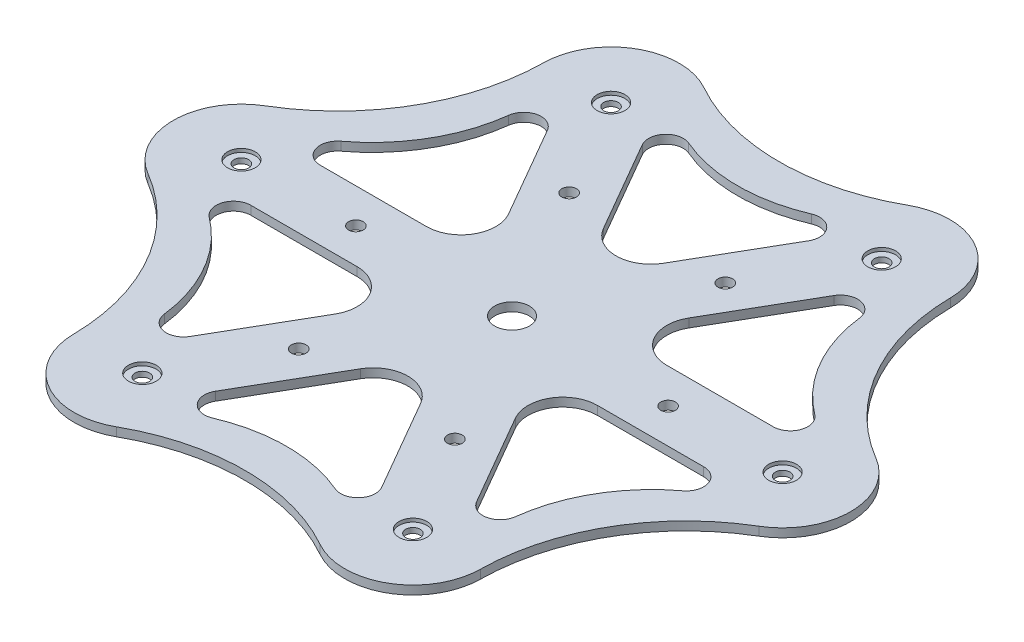
SolidWorks part; units mm, degrees
ref_plane "前视基准面" through (0, 0, 0) normal (0, 0, 1) x (1, 0, 0)
ref_plane "上视基准面" through (0, 0, 0) normal (0, 1, 0) x (1, 0, 0)
ref_plane "右视基准面" through (0, 0, 0) normal (1, 0, 0) x (0, 0, -1)
other "Configuration Table"
sketch "草图2" plane through (0, 0, 0) normal (0, 1, 0) x (1, 0, 0)
  line L1 (45, 0) -> (22.5, 38.9711)
  line L2 (22.5, 38.9711) -> (-22.5, 38.9711)
  line L3 (-22.5, 38.9711) -> (-45, 0)
  line L4 (-45, 0) -> (-22.5, -38.9711)
  line L5 (-22.5, -38.9711) -> (22.5, -38.9711)
  line L6 (22.5, -38.9711) -> (45, 0)
  line L7 (-54.5, 0) -> (-27.25, -47.1984)
  line L8 (-27.25, -47.1984) -> (27.25, -47.1984)
  line L9 (27.25, -47.1984) -> (54.5, 0)
  line L10 (54.5, 0) -> (27.25, 47.1984)
  line L11 (27.25, 47.1984) -> (-27.25, 47.1984)
  line L12 (-27.25, 47.1984) -> (-54.5, 0)
  circle A0 centre (0, 0) radius 38.9711 construction
  circle A1 centre (0, 0) radius 47.1984 construction
  circle A2 centre (0, 0) radius 5
  dimension "D3" = 10
  dimension "D1" = 45
  dimension "D2" = 9.5
extrude "凸台-拉伸1" add sketch "草图2" along normal blind 2.5 contours L5 L6 L1 L2 L3 L4 | L11 L12 L7 L8 L9 L10 L6 L5 L4 L3 L2 L1
sketch "草图3" plane through (0, 2.5, 0) normal (0, 1, 0) x (1, 0, 0)
  line L7 (-45, 0) -> (-22.5, -38.9711) construction
  line L8 (-22.5, -38.9711) -> (22.5, -38.9711) construction
  line L9 (22.5, -38.9711) -> (45, 0) construction
  line L10 (45, 0) -> (22.5, 38.9711) construction
  line L11 (22.5, 38.9711) -> (-22.5, 38.9711) construction
  line L12 (-22.5, 38.9711) -> (-45, 0) construction
  circle A0 centre (0, 0) radius 38.9711 construction
  circle A7 centre (-22.5, 38.9711) radius 2.1
  circle A8 centre (22.5, 38.9711) radius 2.1
  circle A9 centre (45, 0) radius 2.1
  circle A10 centre (22.5, -38.9711) radius 2.1
  circle A11 centre (-22.5, -38.9711) radius 2.1
  circle A12 centre (-45, 0) radius 2.1
  point P23 (0, 0)
  point P24 (0, 0)
  dimension "D2" = 4.2
  dimension "D1" = 45
  dimension "D3" = 6
extrude "切除-拉伸1" cut sketch "草图3" against normal blind 2.5
sketch "草图4" plane through (0, 2.5, 0) normal (0, 1, 0) x (1, 0, 0)
  line L0 (-27.25, 47.1984) -> (-54.5, 0) construction
  line L1 (-54.5, 0) -> (-27.25, -47.1984)
  line L2 (-27.25, -47.1984) -> (27.25, -47.1984)
  line L3 (27.25, -47.1984) -> (54.5, 0)
  line L4 (54.5, 0) -> (27.25, 47.1984)
  line L5 (27.25, 47.1984) -> (-27.25, 47.1984)
  line L6 (-27.25, 47.1984) -> (-54.5, 0)
  line L7 (-100.688, 0) -> (-50.344, -87.1984)
  line L8 (-50.344, -87.1984) -> (50.344, -87.1984)
  line L9 (50.344, -87.1984) -> (100.688, 0)
  line L10 (100.688, 0) -> (50.344, 87.1984)
  line L11 (50.344, 87.1984) -> (-50.344, 87.1984)
  line L12 (-50.344, 87.1984) -> (-100.688, 0)
  circle A0 centre (0, 0) radius 47.1984 construction
  circle A1 centre (0, 0) radius 87.1984 construction
  dimension "D1" = 40
extrude "凸台-拉伸2" add sketch "草图4" against normal up to surface (2.5 mm away) up to face at (-45, 0, 2.1)
sketch "草图5" plane through (0, 2.5, 0) normal (0, 1, 0) x (1, 0, 0)
  line L1 (-78, 0) -> (-39, -67.55) construction
  line L2 (-39, -67.55) -> (39, -67.55) construction
  line L3 (39, -67.55) -> (78, 0) construction
  line L4 (78, 0) -> (39, 67.55) construction
  line L5 (39, 67.55) -> (-39, 67.55) construction
  line L6 (-39, 67.55) -> (-78, 0) construction
  line L7 (-78, 0) -> (0, 0) construction
  circle A0 centre (0, 0) radius 67.55 construction
  circle A1 centre (-39, 67.55) radius 2.1
  circle A2 centre (39, 67.55) radius 2.1
  circle A3 centre (78, 0) radius 2.1
  circle A4 centre (39, -67.55) radius 2.1
  circle A5 centre (-39, -67.55) radius 2.1
  circle A6 centre (-78, 0) radius 2.1
  point P24 (0, 0)
  dimension "D2" = 4.2
  dimension "D1" = 78
  dimension "D3" = 6
extrude "切除-拉伸2" cut sketch "草图5" against normal blind 10
sketch "草图8" plane through (0, 2.5, 0) normal (0, 1, 0) x (1, 0, 0)
  line L0 (50.344, 87.1984) -> (-50.344, 87.1984) construction
  line L1 (-100.688, 0) -> (-50.344, -87.1984) construction
  circle A0 centre (-39, 67.55) radius 19.6484
  circle A5 centre (-78, 0) radius 19.6484
  circle A6 centre (-118.6428, 68.4984) radius 60
  circle A21 centre (39, 67.55) radius 19.6484
  circle A22 centre (78, 0) radius 19.6484
  circle A23 centre (39, -67.55) radius 19.6484
  circle A24 centre (-39, -67.55) radius 19.6484
  circle A25 centre (-78, 0) radius 19.6484
  circle A26 centre (0, 136.9969) radius 60
  circle A27 centre (118.6428, 68.4984) radius 60
  circle A28 centre (118.6428, -68.4984) radius 60
  circle A29 centre (0, -136.9969) radius 60
  circle A30 centre (-118.6428, -68.4984) radius 60
  point P28 (0, 0)
  point P36 (0, 0)
  point P40 (0, 0)
  point P41 (0.1423, 0.0822)
  dimension "D1" = 120
  dimension "D3" = 6
  dimension "D2" = 6
extrude "切除-拉伸3" cut sketch "草图8" against normal blind 10
sketch "草图9" plane through (0, 2.5, 0) normal (0, 1, 0) x (1, 0, 0)
  line L0 (0, 37.5) -> (0, -37.5) construction
  line L1 (-47, 37.5) -> (47, 37.5) construction
  line L2 (-47, 37.5) -> (-47, -37.5) construction
  line L3 (-47, -37.5) -> (47, -37.5) construction
  line L4 (47, 37.5) -> (47, -37.5) construction
  circle A0 centre (-47, 37.5) radius 1.5
  circle A1 centre (47, 37.5) radius 1.5
  circle A2 centre (47, -37.5) radius 1.5
  circle A3 centre (-47, -37.5) radius 1.5
  dimension "D3" = 3
  dimension "D1" = 75
  dimension "D2" = 94
extrude "切除-拉伸4" [suppressed] cut sketch "草图9" against normal blind 10
sketch "草图10" plane through (0, 2.5, 0) normal (0, 1, 0) x (1, 0, 0)
  circle A0 centre (-78, 0) radius 4
  circle A1 centre (-39, 67.55) radius 4
  circle A2 centre (39, 67.55) radius 4
  circle A3 centre (78, 0) radius 4
  circle A4 centre (39, -67.55) radius 4
  circle A5 centre (-39, -67.55) radius 4
  point P15 (0, 0)
  dimension "D1" = 8
  dimension "D2" = 6
extrude "切除-拉伸5" cut sketch "草图10" against normal blind 1
sketch "草图11" plane through (0, 0, 0) normal (0, -1, 0) x (1, 0, 0)
  line L0 (-66.6812, -38.4984) -> (0, 0) construction
  line L1 (-78, 0) -> (0, 0) construction
  line L2 (0, 0) -> (-39, -67.55) construction
  line L3 (-95.2628, -10) -> (-17.3205, -10)
  line L4 (-17.3205, -10) -> (-56.2917, -77.5)
  arc A0 (-58.647, -67.784) -> (-88.0261, -16.8978) centre (-118.6428, -68.4984) ccw construction
  circle A1 centre (-95.2628, -55) radius 45
  circle A2 centre (-34.641, -20) radius 10
  circle A3 centre (-65.2628, -15) radius 5
  circle A4 centre (-45.6218, -49.0192) radius 5
  dimension "D2" = 90
  dimension "D3" = 10
  dimension "D4" = 20
  dimension "D1" = 20
extrude "切除-拉伸6" cut sketch "草图11" against normal through all contours A4 L4 A2 L3 A3 A1 | A2 | A3 | A4
pattern_circular "阵列(圆周)1" count 6 over 360 about axis through (0, 0, 0) along (0, 1, 0) of "切除-拉伸6"
